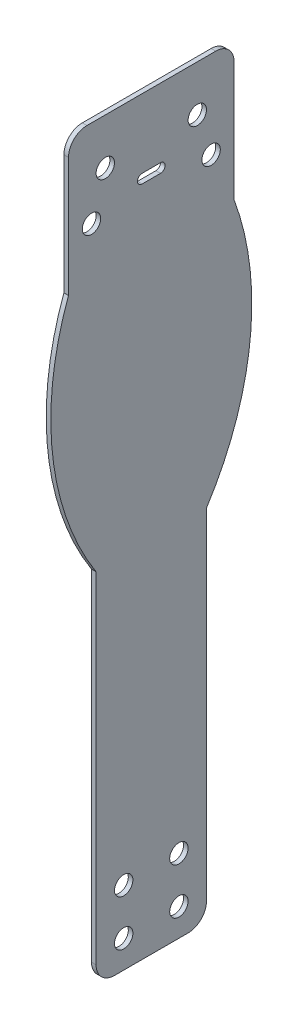
SolidWorks part; units mm, degrees
material "PVC 0.007 Plasticized"
ref_plane "Front Plane" through (0, 0, 0) normal (0, 0, 1) x (1, 0, 0)
ref_plane "Top Plane" through (0, 0, 0) normal (0, 1, 0) x (1, 0, 0)
ref_plane "Right Plane" through (0, 0, 0) normal (1, 0, 0) x (0, 0, -1)
sketch "Sketch1" plane through (0, 0, 0) normal (1, 0, 0) x (0, 0, -1)
  line L0 (12, -163) -> (12, -85)
  line L1 (-18, 0) -> (18, 0)
  line L2 (-18, 0) -> (-18, -163) construction
  line L3 (-18, -163) -> (18, -163) construction
  line L4 (18, 0) -> (18, -163) construction
  line L5 (-18, 0) -> (18, -163) construction
  line L6 (-18, -163) -> (18, 0) construction
  line L7 (-12, -163) -> (-12, -85)
  line L8 (12, -85) -> (-12, -85) construction
  line L9 (18, -30) -> (-18, -30) construction
  line L10 (18, 0) -> (18, -30)
  line L11 (-18, 0) -> (-18, -30)
  line L12 (-21.8408, -51.4826) -> (21.8408, -51.4826) construction
  line L13 (12, -163) -> (-12, -163)
  arc A0 (18, -30) -> (12, -85) centre (-40.1592, -51.4826) cw
  arc A1 (-18, -30) -> (-12, -85) centre (40.1592, -51.4826) ccw
  point P4 (0, -81.5)
  point P5 (0, 0)
  point P10 (0, -85)
  point P18 (0, 0)
  point P19 (0, 0)
  point P20 (0, 0)
  dimension "D6" = 62
  dimension "D7" = 62
  dimension "D1" = 30
  dimension "D2" = 36
  dimension "D3" = 24
  dimension "D4" = 163
  dimension "D5" = 55
  dimension "D8" = 43.6815
extrude "Boss-Extrude1" add sketch "Sketch1" along normal blind 1 contours L1 L10 A0 L0 L13 L7 A1 L11
hole_wizard "Ø4.0 (4) Diameter Hole3" positions "Sketch6" profile "Sketch7" hole size "Ø4.0" standard "ISO" end condition through all
sketch "Sketch6" plane through (0, 0, 0) normal (-1, 0, 0) x (0, 0, 1)
  point P0 (10, -10)
  point P3 (-10, -10)
sketch "Sketch7" plane through (0, -10, 10) normal (0, 1, 0) x (0, 0, 1)
  line L0 (0, 0) -> (0, 1)
  line L1 (0, 1) -> (2, 1)
  line L2 (2, 1) -> (2, 0)
  line L5 (2, 0) -> (0, 0)
  line L11 (0, -6.35) -> (0, 107.95) construction
  dimension "Thru Hole Dia." = 4
  dimension "Thru Hole Depth" = 1
hole_wizard "Ø4.0 (4) Diameter Hole2" positions "Sketch8" profile "Sketch9" hole size "Ø4.0" standard "ISO" end condition through all
sketch "Sketch8" plane through (0, 0, 0) normal (-1, 0, 0) x (0, 0, 1)
  point P4 (-13, -19)
  point P7 (13, -19)
sketch "Sketch9" plane through (0, -19, -13) normal (0, 1, 0) x (0, 0, 1)
  line L0 (0, 0) -> (0, 1)
  line L1 (0, 1) -> (2, 1)
  line L2 (2, 1) -> (2, 0)
  line L5 (2, 0) -> (0, 0)
  line L11 (0, -6.35) -> (0, 107.95) construction
  dimension "Thru Hole Dia." = 4
  dimension "Thru Hole Depth" = 1
sketch "Sketch10" plane through (1, 0, 0) normal (1, 0, 0) x (0, 0, -1)
  line L0 (-2, -16) -> (2, -16) construction
  line L1 (-2, -15) -> (2, -15)
  line L2 (-2, -17) -> (2, -17)
  line L3 (-18, 0) -> (18, 0) construction
  arc A0 (-2, -15) -> (-2, -17) centre (-2, -16) ccw
  arc A1 (2, -17) -> (2, -15) centre (2, -16) ccw
  point P2 (0, -16)
  dimension "D2" = 1
  dimension "D1" = 4
  dimension "D3" = 16
extrude "Cut-Extrude1" cut sketch "Sketch10" against normal through all
hole_wizard "Ø4.0 (4) Diameter Hole1" positions "Sketch12" profile "Sketch11" hole size "Ø4.0" standard "ISO" end condition through all
sketch "Sketch12" plane through (1, 0, 0) normal (1, 0, 0) x (0, 0, -1)
  line L1 (12, -163) -> (-12, -163) construction
  point P0 (-6, -157)
  point P2 (6, -157)
  dimension "D1" = 12
  dimension "D2" = 6
  dimension "D3" = 6
sketch "Sketch11" plane through (1, -157, 6) normal (0, 1, 0) x (0, 0, -1)
  line L0 (0, 0) -> (0, 1)
  line L1 (0, 1) -> (2, 1)
  line L2 (2, 1) -> (2, 0)
  line L5 (2, 0) -> (0, 0)
  line L11 (0, -6.35) -> (0, 107.95) construction
  dimension "Thru Hole Dia." = 4
  dimension "Thru Hole Depth" = 1
pattern_linear "LPattern1" count 2 spacing 10 along (0, 1, 0) of "Ø4.0 (4) Diameter Hole1"
fillet "Fillet1" radius 4 4 edges at (0.5, -163, -12) (0.5, -163, 12) (0.5, 0, 18) (0.5, 0, -18)
